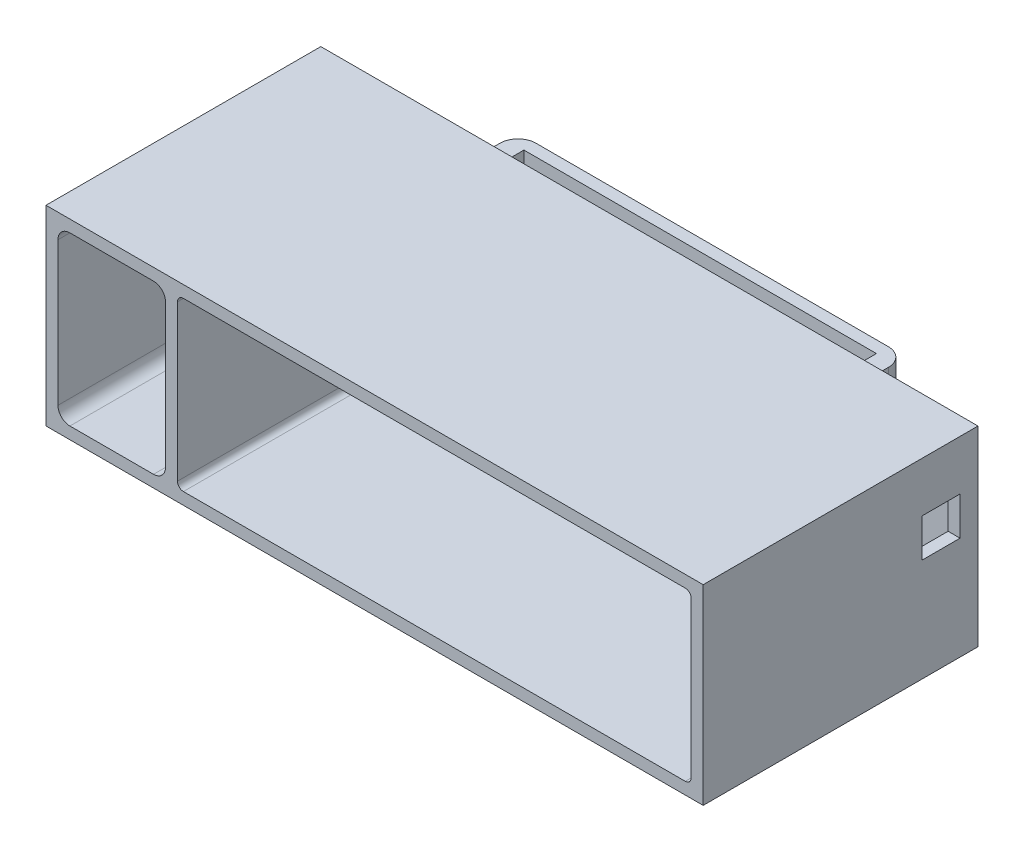
SolidWorks part; units mm, degrees
ref_plane "Plan de face" through (0, 0, 0) normal (0, 0, 1) x (1, 0, 0)
ref_plane "Plan de dessus" through (0, 0, 0) normal (0, 1, 0) x (1, 0, 0)
ref_plane "Plan de droite" through (0, 0, 0) normal (1, 0, 0) x (0, 0, -1)
sketch "Esquisse1" plane through (0, 0, 0) normal (0, 0, 1) x (1, 0, 0)
  line L0 (0, 0) -> (90, 0)
  line L1 (90, 0) -> (90, 32)
  line L2 (90, 32) -> (0, 32)
  line L3 (0, 32) -> (0, 0)
  dimension "D1" = 90
  dimension "D2" = 32
extrude "Boss.-Extru.1" add sketch "Esquisse1" along normal blind 2
sketch "Esquisse2" plane through (0, 0, 2) normal (0, 0, 1) x (1, 0, 0)
  line L0 (0, 0) -> (90, 0)
  line L1 (2, 30) -> (88, 30)
  line L2 (88, 30) -> (88, 2)
  line L3 (88, 2) -> (2, 2)
  line L4 (2, 2) -> (2, 30)
  line L5 (90, 32) -> (0, 32) construction
  line L6 (90, 0) -> (90, 32) construction
  line L7 (0, 0) -> (90, 0) construction
  line L8 (0, 32) -> (0, 0) construction
  line L9 (90, 0) -> (90, 32)
  line L10 (90, 32) -> (0, 32)
  line L11 (0, 32) -> (0, 0)
  dimension "D1" = 2
  dimension "D2" = 2
  dimension "D3" = 2
  dimension "D4" = 2
extrude "Boss.-Extru.3" add sketch "Esquisse2" along normal blind 45
sketch "Esquisse3" plane through (90, 0, 0) normal (1, 0, 0) x (0, 0, -1)
  line L0 (0, 17.24) -> (-4, 17.24)
  line L4 (-4, 17.24) -> (-4, 23.65)
  line L6 (-4, 17.24) -> (-10.41, 17.24)
  line L7 (-10.41, 17.24) -> (-10.5642, 17.167)
  line L8 (-10.41, 17.24) -> (-10.41, 23.65)
  line L9 (-10.41, 23.65) -> (-4, 23.65)
  dimension "D1" = 6.41
  dimension "D4" = 4
extrude "Enlèv. mat.-Extru.1" cut sketch "Esquisse3" against normal up to next contours L9 L8 L6 L4
fillet "Congé3" radius 1 8 edges at (2, 30, 24.5) (2, 2, 24.5) (2, 16, 2) (45, 30, 2) (88, 30, 24.5) (88, 2, 24.5) (88, 16, 2) (45, 2, 2)
sketch "Esquisse7" plane through (0, 0, 0) normal (0, 0, -1) x (-1, 0, 0)
  line L0 (-90, 0) -> (-90, 32)
  line L1 (-90, 32) -> (0, 32)
  line L2 (0, 32) -> (0, 0)
  line L3 (0, 0) -> (-90, 0)
  line L4 (-5, 4) -> (-70, 4)
  line L5 (-70, 4) -> (-70, 28)
  line L6 (-70, 28) -> (-5, 28)
  line L7 (-5, 28) -> (-5, 4)
  dimension "D1" = 5
  dimension "D2" = 20
  dimension "D3" = 4
  dimension "D4" = 4
chamfer "Chanfrein8" distance 1 angle 45 4 edges at (0, 16, 0) (45, 0, 0) (90, 16, 0) (45, 32, 0)
extrude "Boss.-Extru.8" add sketch "Esquisse7" along normal blind 7 contours L7 L4 L5 L6
fillet "Congé11" radius 3 1 edges at (5, 16, -7)
fillet "Congé12" radius 3 1 edges at (70, 16, -7)
sketch "Esquisse17" plane through (0, 28, 0) normal (0, 1, 0) x (1, 0, 0)
  line L0 (8, 0) -> (8, 5)
  line L1 (70, 0) -> (5, 0) construction
  line L2 (8, 5) -> (67, 5)
  line L3 (67, 5) -> (67, 0)
  line L4 (67, 0) -> (8, 0)
  line L5 (5, 4) -> (5, 0) construction
  line L6 (70, 4) -> (70, 0) construction
  line L7 (67, 7) -> (8, 7) construction
  point P8 (5, 2)
  dimension "D1" = 3
  dimension "D2" = 3
  dimension "D3" = 2
extrude "Enlèv. mat.-Extru.6" cut sketch "Esquisse17" against normal blind 24 contours L4 L0 L2 L3
sketch "Esquisse20" plane through (0, 0, 0) normal (-1, 0, 0) x (0, 0, 1)
  line L0 (47, 32) -> (47, 0)
  line L1 (47, 0) -> (1, 0)
  line L2 (1, 0) -> (1, 32)
  line L3 (1, 32) -> (47, 32)
extrude "Boss.-Extru.10" add sketch "Esquisse20" along normal blind 20
sketch "Esquisse21" plane through (0, 0, 47) normal (0, 0, 1) x (1, 0, 0)
  line L0 (0, 30) -> (0, 2)
  line L1 (0, 2) -> (-18, 2)
  line L2 (-18, 2) -> (-18, 30)
  line L3 (-18, 30) -> (0, 30)
  line L5 (-20, 0) -> (90, 0) construction
  line L6 (90, 32) -> (-20, 32) construction
  dimension "D1" = 2
  dimension "D2" = 2
  dimension "D3" = 18
extrude "Enlèv. mat.-Extru.7" cut sketch "Esquisse21" against normal blind 43
fillet "Congé13" radius 2 1 edges at (0, 30, 25.5)
fillet "Congé14" radius 2 1 edges at (-18, 30, 25.5)
fillet "Congé15" radius 2 1 edges at (0, 2, 25.5)
fillet "Congé16" radius 2 1 edges at (-18, 2, 25.5)
sketch "Esquisse22" plane through (2, 0, 0) normal (1, 0, 0) x (0, 0, -1)
  line L0 (-7, 24) -> (-7, 8)
  line L1 (-7, 8) -> (-4, 8)
  line L2 (-4, 8) -> (-4, 24)
  line L3 (-4, 24) -> (-7, 24)
  line L4 (-3, 3) -> (-3, 29) construction
  line L5 (-3, 29) -> (-47, 29) construction
  line L6 (-47, 3) -> (-3, 3) construction
  line L7 (-47, 29) -> (-47, 3) construction
  dimension "D1" = 1
  dimension "D2" = 5
  dimension "D3" = 5
  dimension "D4" = 40
extrude "Enlèv. mat.-Extru.8" cut sketch "Esquisse22" against normal blind 2
